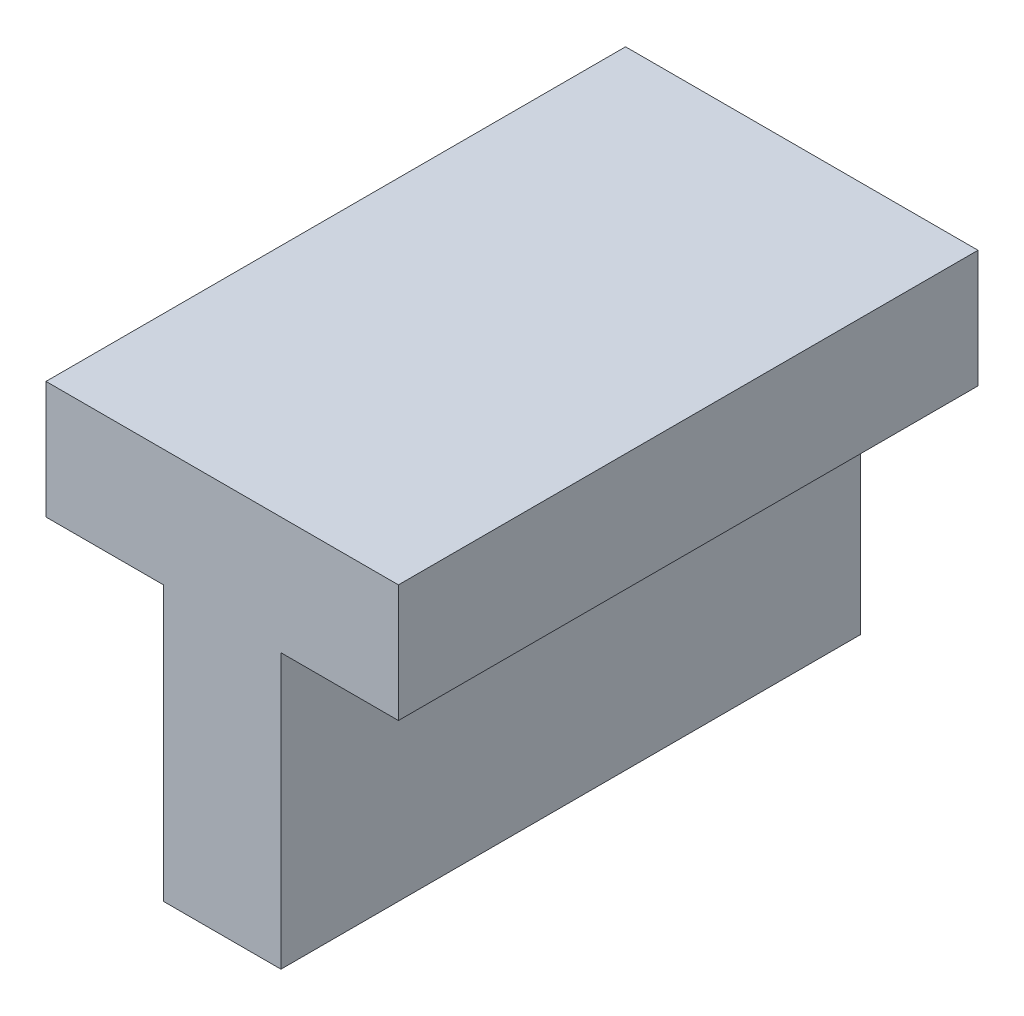
SolidWorks part; units mm, degrees
ref_plane "Front Plane" through (0, 0, 0) normal (0, 0, 1) x (1, 0, 0)
ref_plane "Top Plane" through (0, 0, 0) normal (0, 1, 0) x (1, 0, 0)
ref_plane "Right Plane" through (0, 0, 0) normal (1, 0, 0) x (0, 0, -1)
sketch "Sketch1" plane through (0, 0, 0) normal (0, 0, 1) x (1, 0, 0)
  line L0 (-1.5, -10) -> (1.5, -10)
  line L1 (1.5, -10) -> (1.5, -3)
  line L2 (1.5, -3) -> (4.5, -3)
  line L3 (4.5, -3) -> (4.5, 0)
  line L4 (4.5, 0) -> (-4.5, 0)
  line L5 (-4.5, 0) -> (-4.5, -3)
  line L6 (-4.5, -3) -> (-1.5, -3)
  line L7 (-1.5, -3) -> (-1.5, -10)
  point P6 (0, -10)
  dimension "D1" = 3
  dimension "D2" = 7
  dimension "D3" = 3
  dimension "D4" = 3
extrude "Boss-Extrude1" add sketch "Sketch1" along normal blind 14.8
